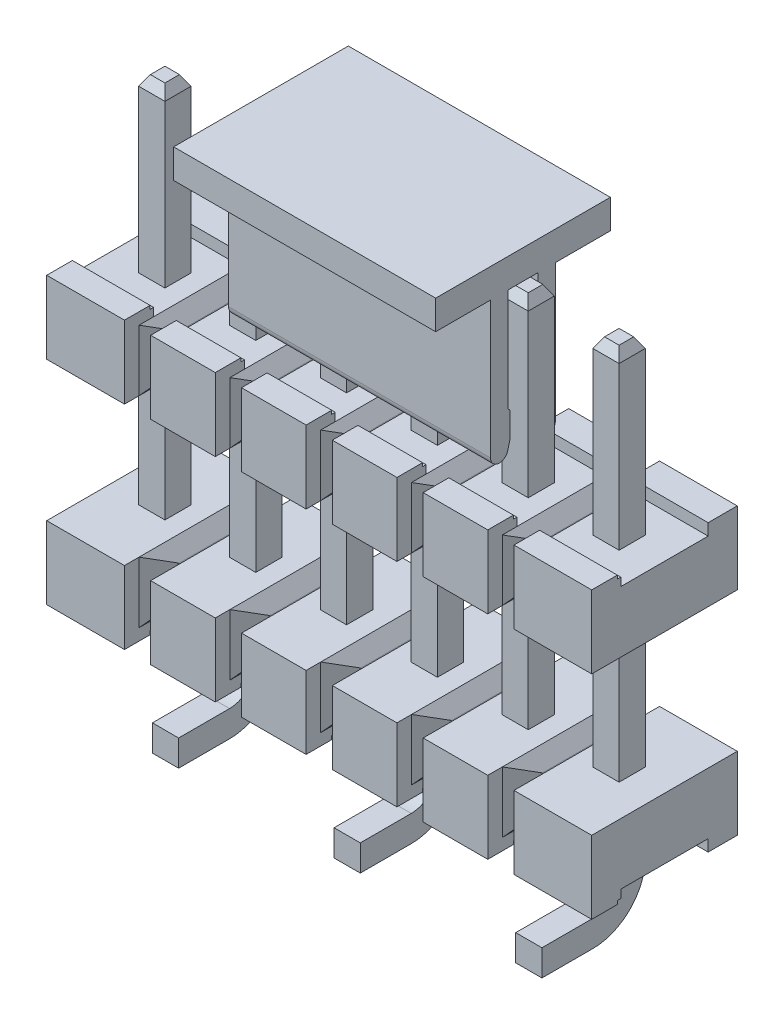
SolidWorks part; units mm, degrees
ref_plane "Front" through (0, 0, 0) normal (0, 0, 1) x (1, 0, 0)
ref_plane "Top" through (0, 0, 0) normal (0, 1, 0) x (1, 0, 0)
ref_plane "Side" through (0, 0, 0) normal (1, 0, 0) x (0, 0, -1)
sketch "Sketch1" plane through (0, 0, 0) normal (0, 1, 0) x (1, 0, 0)
  line L0 (-11.8872, -3.175) -> (11.8872, 3.175) construction
  line L1 (-11.8872, 3.175) -> (11.8872, 3.175)
  line L2 (-11.8872, 3.175) -> (-11.8872, -3.175)
  line L3 (-11.8872, -3.175) -> (11.8872, -3.175)
  line L4 (11.8872, 3.175) -> (11.8872, -3.175)
  dimension "D1" = 23.7744
  dimension "D2" = 6.35
extrude "Body" add sketch "Sketch1" along normal blind 3.175
sketch "Sketch2" plane through (-11.8872, 0, 0) normal (-1, 0, 0) x (0, 0, 1)
  line L0 (1.905, 0.1524) -> (2.0574, 0.1524)
  line L1 (-3.175, 0) -> (3.175, 0) construction
  line L2 (2.0574, 0.1524) -> (2.0574, 0)
  line L3 (-1.905, 0) -> (-1.905, 0.508)
  line L4 (-1.905, 0.508) -> (1.905, 0.508)
  line L5 (1.905, 0.508) -> (1.905, 0.1524)
  line L6 (-1.905, 0) -> (2.0574, 0)
  line L7 (3.175, 3.175) -> (3.175, 0) construction
  line L8 (0, 0) -> (0, 3.175) construction
  line L9 (-3.175, 3.175) -> (3.175, 3.175) construction
  dimension "D1" = 1.27
  dimension "D2" = 0.508
  dimension "D3" = 0.1524
  dimension "D4" = 0.1524
extrude "Bottom Cut" cut sketch "Sketch2" against normal up to surface (23.7744 mm away) up to face at (11.8872, 1.5875, 0)
sketch "Sketch3" plane through (0, 3.175, 0) normal (0, 1, 0) x (1, 0, 0)
  line L0 (0, 0) -> (-11.8872, 0) construction
  line L1 (-11.8872, 3.175) -> (-11.8872, -3.175) construction
  line L2 (-7.3533, 3.175) -> (-7.3533, 2.54)
  line L3 (11.8872, 3.175) -> (-11.8872, 3.175) construction
  line L4 (-7.3533, 3.175) -> (-8.4963, 3.175)
  line L5 (-8.4963, 3.175) -> (-8.4963, 2.54)
  line L6 (-7.9248, 3.175) -> (-7.9248, 1.3462) construction
  line L7 (-8.4963, 2.54) -> (-8.0441, 1.3026)
  line L8 (-7.3533, 2.54) -> (-7.8055, 1.3026)
  line L9 (-7.3533, -2.54) -> (-7.8055, -1.3026)
  line L10 (-8.4963, -2.54) -> (-8.0441, -1.3026)
  line L11 (-8.4963, -3.175) -> (-8.4963, -2.54)
  line L12 (-7.3533, -3.175) -> (-8.4963, -3.175)
  line L13 (-7.3533, -3.175) -> (-7.3533, -2.54)
  arc A0 (-8.0441, 1.3026) -> (-7.8055, 1.3026) centre (-7.9248, 1.3462) ccw
  arc A1 (-8.0441, -1.3026) -> (-7.8055, -1.3026) centre (-7.9248, -1.3462) cw
  dimension "D1" = 0.254
  dimension "D2" = 0.635
  dimension "D3" = 1.9558
  dimension "D4" = 1.143
  dimension "D5" = 3.9624
extrude "Rib Cut 1" cut sketch "Sketch3" against normal blind 3.175
sketch "Sketch4" plane through (0, 0, 3.175) normal (0, 0, 1) x (1, 0, 0)
  line L0 (-8.4963, 3.175) -> (-7.3533, 3.175)
  line L2 (-11.8872, 3.175) -> (-8.4963, 3.175) construction
  line L3 (-7.3533, 3.175) -> (11.8872, 3.175) construction
  line L4 (-7.9248, 3.175) -> (-7.9248, 2.6162) construction
  line L5 (-8.4963, 3.175) -> (-8.0269, 2.5407)
  line L6 (-7.3533, 3.175) -> (-7.8227, 2.5407)
  line L7 (-7.8055, 3.175) -> (-8.0441, 3.175) construction
  line L8 (-7.3533, 0) -> (-7.3533, 0.508)
  line L9 (-7.3533, 0) -> (-7.3533, 3.175) construction
  line L10 (-7.3533, 0) -> (-8.4963, 0)
  line L11 (-8.4963, 0) -> (-8.4963, 0.508)
  line L12 (-8.4963, 0) -> (-8.4963, 3.175) construction
  line L13 (-7.9248, 2.6162) -> (-7.9248, 1.0668) construction
  line L14 (-7.3533, 0.508) -> (-7.8227, 1.1423)
  line L15 (-8.4963, 0.508) -> (-8.0269, 1.1423)
  arc A0 (-8.0269, 2.5407) -> (-7.8227, 2.5407) centre (-7.9248, 2.6162) ccw
  arc A1 (-7.8227, 1.1423) -> (-8.0269, 1.1423) centre (-7.9248, 1.0668) ccw
  dimension "D3" = 0.127
  dimension "D4" = 0.127
  dimension "D5" = 0.5588
  dimension "D1" = 1.143
  dimension "D2" = 0.6858
  dimension "D6" = 0.508
extrude "Rib Cut 2" cut sketch "Sketch4" against normal blind 6.35
pattern_linear "Rib Pattern" count 5 spacing 3.9624 along (1, 0, 0) of "Rib Cut 1", "Rib Cut 2"
ref_plane "Body Mirror Plane" through (0, 6.223, 0) normal (0, 1, 0) x (-1, 0, 0)
mirror "Body Mirror" about plane through (0, 6.223, 0) normal (0, 1, 0) of bodies 105
sketch "Sketch5" plane through (0, 3.175, 0) normal (0, 1, 0) x (1, 0, 0)
  line L0 (-9.906, -0.5715) -> (-9.906, 0.5715) construction
  line L1 (-10.4775, 0.5715) -> (-9.3345, 0.5715)
  line L2 (-10.4775, 0.5715) -> (-10.4775, -0.5715)
  line L3 (-10.4775, -0.5715) -> (-9.3345, -0.5715)
  line L4 (-9.3345, 0.5715) -> (-9.3345, -0.5715)
  line L5 (-10.4775, 0) -> (-9.3345, 0) construction
  line L6 (-11.8872, 3.175) -> (-11.8872, -3.175) construction
  dimension "D1" = 1.143
  dimension "D2" = 1.9812
extrude "Contact" add sketch "Sketch5" along normal blind 16.256
chamfer "Contact Chamfer" distance 0.254 angle 60 4 edges at (-9.906, 19.431, -0.5715) (-9.3345, 19.431, 0) (-9.906, 19.431, 0.5715) (-10.4775, 19.431, 0)
pattern_linear "Contact Pattern" count 6 spacing 3.9624 along (1, 0, 0) of "Contact", "Contact Chamfer"
sketch "Sketch6" plane through (-10.4775, 0, 0) normal (-1, 0, 0) x (0, 0, 1)
  line L0 (1.905, 0.508) -> (-1.905, 0.508) construction
  line L1 (-0.5715, 0.508) -> (0.5715, 0.508)
  line L2 (-0.5715, 0.508) -> (-0.5715, -2.286)
  line L3 (-0.5715, -2.286) -> (0.5715, -2.286)
  line L4 (0.5715, 0.508) -> (0.5715, -2.286)
  line L5 (0, 0) -> (0, 0.508) construction
  dimension "D1" = 1.143
  dimension "D2" = 2.286
ref_plane "SM Plane" through (-6.5151, 0, 0) normal (-1, 0, 0) x (0, 0, 1)
sketch "Sketch8" plane through (-10.4775, 0, 0) normal (-1, 0, 0) x (0, 0, 1)
  line L0 (0, 0.508) -> (0, -5.5682) construction
  line L1 (-0.5715, 0.508) -> (0.5715, 0.508)
  line L2 (-0.5715, 0.508) -> (-0.5715, -0.254)
  line L3 (-3.937, -1.9685) -> (2.7349, -1.9685) construction
  line L4 (0.5715, 0.508) -> (0.5715, -0.254)
  line L5 (-1.7145, -2.54) -> (-3.937, -2.54)
  line L6 (-3.175, 0) -> (-1.905, 0) construction
  line L7 (-1.7145, -1.397) -> (-3.937, -1.397)
  line L8 (-3.937, -2.54) -> (-3.937, -1.397)
  line L10 (1.905, 0.508) -> (-1.905, 0.508) construction
  arc A0 (-1.7145, -1.397) -> (-0.5715, -0.254) centre (-1.7145, -0.254) ccw
  arc A1 (-1.7145, -2.54) -> (0.5715, -0.254) centre (-1.7145, -0.254) ccw
  dimension "D1" = 2.286
  dimension "D2" = 1.143
  dimension "D3" = 2.54
  dimension "D4" = 3.937
extrude "SM 1" add sketch "Sketch8" against normal blind 1.143
sketch "Sketch7" plane through (-6.5151, 0, 0) normal (-1, 0, 0) x (0, 0, 1)
  line L0 (-0.5715, 0.508) -> (-0.5715, -0.254)
  line L1 (-0.5715, 0.508) -> (0.5715, 0.508)
  line L2 (0.5715, 0.508) -> (0.5715, -0.254)
  line L3 (1.7145, -1.397) -> (3.937, -1.397)
  line L4 (3.937, -1.397) -> (3.937, -2.54)
  line L5 (3.937, -2.54) -> (1.7145, -2.54)
  line L6 (0, 0.508) -> (0, -5.6019) construction
  line L7 (3.937, -1.9685) -> (-10.4323, -1.9685) construction
  line L9 (1.905, 0.508) -> (-1.905, 0.508) construction
  line L10 (2.0574, 0) -> (3.175, 0) construction
  arc A0 (0.5715, -0.254) -> (1.7145, -1.397) centre (1.7145, -0.254) ccw
  arc A1 (-0.5715, -0.254) -> (1.7145, -2.54) centre (1.7145, -0.254) ccw
  dimension "D1" = 2.286
  dimension "D2" = 1.143
  dimension "D3" = 2.54
  dimension "D4" = 3.937
extrude "SM 2" add sketch "Sketch7" against normal blind 1.143
pattern_linear "SM 1 Pattern" count 3 spacing 7.9248 along (1, 0, 0) of "SM 1"
pattern_linear "SM 2 Pattern" count 3 spacing 7.9248 along (1, 0, 0) of "SM 2"
sketch "Sketch9" plane through (0, 0, 0) normal (1, 0, 0) x (0, 0, -1)
  line L0 (-3.81, 20.701) -> (3.81, 20.701)
  line L1 (3.81, 20.701) -> (3.81, 19.431)
  line L2 (3.81, 19.431) -> (1.4145, 19.431)
  line L3 (1.4145, 19.431) -> (1.4145, 13.462)
  line L4 (0, 0) -> (0, 27.6274) construction
  line L5 (-0.6525, 19.431) -> (0.6525, 19.431)
  line L6 (0.6525, 19.431) -> (0.6525, 14.9337)
  line L7 (0.6525, 14.9337) -> (0.4508, 14.732)
  line L8 (0.4508, 14.732) -> (0.4508, 14.224)
  line L9 (0.4508, 14.224) -> (0.6638, 13.3698)
  line L10 (0.4508, 14.478) -> (2.0541, 14.478) construction
  line L12 (-0.4508, 14.224) -> (-0.6638, 13.3698)
  line L13 (-0.4508, 14.732) -> (-0.4508, 14.224)
  line L14 (-0.6525, 14.9337) -> (-0.4508, 14.732)
  line L15 (-0.6525, 19.431) -> (-0.6525, 14.9337)
  line L16 (-1.4145, 19.431) -> (-1.4145, 13.462)
  line L17 (-3.81, 19.431) -> (-1.4145, 19.431)
  line L18 (-3.81, 20.701) -> (-3.81, 19.431)
  line L19 (-0.3175, 19.431) -> (0.3175, 19.431) construction
  arc A0 (0.6638, 13.3698) -> (1.4145, 13.462) centre (1.0335, 13.462) ccw
  arc A1 (-0.6638, 13.3698) -> (-1.4145, 13.462) centre (-1.0335, 13.462) cw
  point P26 (0, 19.431)
  point P29 (0, 20.701)
  dimension "D1" = 0.762
  dimension "D2" = 3.81
  dimension "D3" = 1.27
  dimension "D4" = 7.62
  dimension "D5" = 0.762
  dimension "D6" = 0.762
  dimension "D7" = 45
  dimension "D8" = 0.508
  dimension "D9" = 14
  dimension "D10" = 0.4508
extrude "PPP" add sketch "Sketch9" along normal mid plane 11.43
